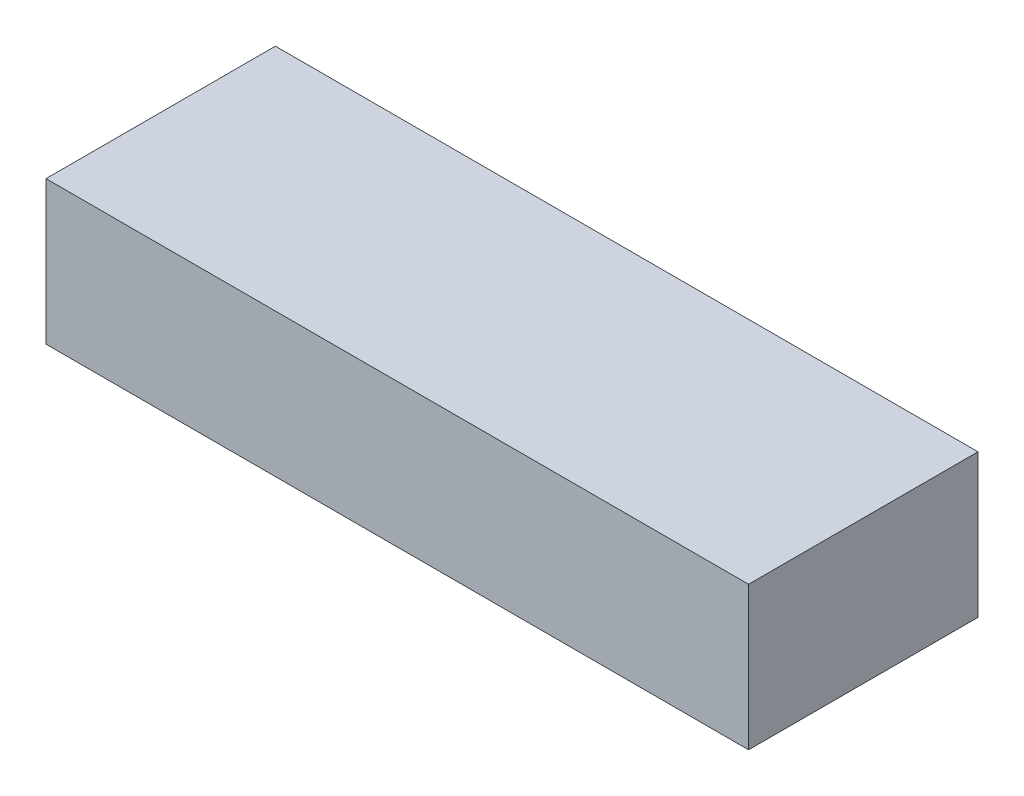
SolidWorks part; units mm, degrees
ref_plane "Front" through (0, 0, 0) normal (0, 0, 1) x (1, 0, 0)
ref_plane "Top" through (0, 0, 0) normal (0, 1, 0) x (1, 0, 0)
ref_plane "Right" through (0, 0, 0) normal (1, 0, 0) x (0, 0, -1)
sketch "Sketch1" plane through (0, 0, 0) normal (0, 1, 0) x (1, 0, 0)
  line L1 (0, 0) -> (49, 0)
  line L2 (0, 0) -> (0, 16)
  line L3 (0, 16) -> (49, 16)
  line L4 (49, 0) -> (49, 16)
  dimension "D1" = 49
  dimension "D2" = 16
extrude "Boss-Extrude1" add sketch "Sketch1" along normal blind 10 contours L2 L3 L4 L1
